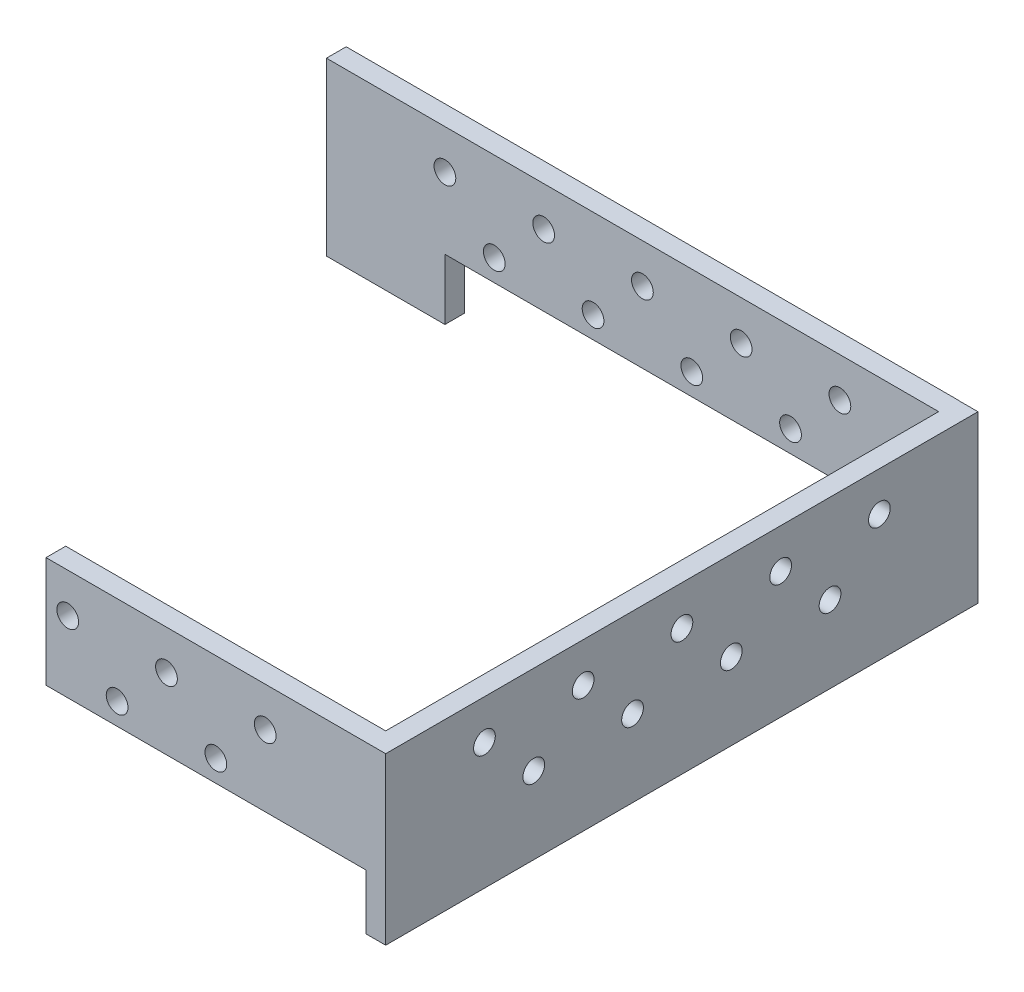
SolidWorks part; units mm, degrees
ref_plane "Front Plane" through (0, 0, 0) normal (0, 0, 1) x (1, 0, 0)
ref_plane "Top Plane" through (0, 0, 0) normal (0, 1, 0) x (1, 0, 0)
ref_plane "Right Plane" through (0, 0, 0) normal (1, 0, 0) x (0, 0, -1)
ref_plane "Plane1" through (-5, 0, 0) normal (-1, 0, 0) x (0, -1, 0)
sketch "Sketch1" plane through (-5, 0, 0) normal (-1, 0, 0) x (0, -1, 0)
  line L0 (42, 0) -> (0, 0)
  line L1 (0, 0) -> (0, -145.1613)
  line L2 (0, -145.1613) -> (42, -145.1613)
  line L3 (42, -145.1613) -> (42, 0)
  dimension "D1" = 42
extrude "Boss-Extrude1" add sketch "Sketch1" against normal blind 5
ref_plane "Plane2" through (0, 0, -150) normal (0, 0, -1) x (-1, 0, 0)
sketch "Sketch2" plane through (0, 0, -150) normal (0, 0, -1) x (-1, 0, 0)
  line L0 (130, -43.4) -> (160, -43.4)
  line L1 (160, -43.4) -> (160, 0)
  line L2 (160, 0) -> (5, 0)
  line L3 (5, 0) -> (5, -28)
  line L4 (5, -28) -> (130, -28)
  line L5 (130, -28) -> (130, -43.4)
extrude "Boss-Extrude2" add sketch "Sketch2" against normal blind 5
sketch "Sketch3" plane through (-5, 0, 0) normal (-1, 0, 0) x (0, 0, 1)
  line L0 (0, -28) -> (-5, -28)
  line L1 (-5, -28) -> (-5, 0)
  line L2 (-5, 0) -> (0, 0)
  line L3 (0, 0) -> (0, -28)
extrude "Boss-Extrude3" add sketch "Sketch3" along normal blind 81
hole_wizard "Ø5.5 (5.5) Diameter Hole1" positions "Sketch5" profile "Sketch4" hole size "Ø5.5" standard "ANSI Metric" end condition through all
sketch "Sketch5" plane through (-5, 0, 0) normal (-1, 0, 0) x (0, 0, 1)
  point P0 (-37.5, -22.5)
  point P1 (-25, -10)
  point P2 (-50, -10)
  point P3 (-62.5, -22.5)
  point P4 (-75, -10)
  point P5 (-87.5, -22.5)
  point P6 (-112.5, -22.5)
  point P7 (-100, -10)
  point P8 (-125, -10)
sketch "Sketch4" plane through (-5, -22.5, -37.5) normal (0, 1, 0) x (0, 0, 1)
  line L0 (0, 0) -> (0, 5)
  line L1 (0, 5) -> (2.75, 5)
  line L2 (2.75, 5) -> (2.75, 0)
  line L5 (2.75, 0) -> (0, 0)
  line L11 (0, -6.35) -> (0, 107.95) construction
  dimension "Thru Hole Dia." = 5.5
  dimension "Thru Hole Depth" = 5
hole_wizard "Ø5.5 (5.5) Diameter Hole2" positions "Sketch7" profile "Sketch6" hole size "Ø5.5" standard "ANSI Metric"
sketch "Sketch7" plane through (0, 0, -145) normal (0, 0, 1) x (1, 0, 0)
  point P0 (-30, -10)
  point P1 (-42.5, -22.5)
  point P2 (-67.5, -22.5)
  point P3 (-55, -10)
  point P4 (-80, -10)
  point P5 (-92.5, -22.5)
  point P6 (-117.5, -22.5)
  point P7 (-105, -10)
  point P8 (-130, -10)
sketch "Sketch6" plane through (-30, -10, -145) normal (1, 0, 0) x (0, -1, 0)
  line L0 (0, 0) -> (0, 5)
  line L1 (0, 5) -> (2.75, 5)
  line L2 (2.75, 5) -> (2.75, 0)
  line L5 (2.75, 0) -> (0, 0)
  line L11 (0, -6.35) -> (0, 107.95) construction
  dimension "Thru Hole Dia." = 5.5
  dimension "Thru Hole Depth" = 5
hole_wizard "Ø5.5 (5.5) Diameter Hole3" positions "Sketch9" profile "Sketch8" hole size "Ø5.5" standard "ANSI Metric"
sketch "Sketch9" plane through (0, 0, -5) normal (0, 0, -1) x (-1, 0, 0)
  point P0 (80.5, -10)
  point P1 (68, -22.5)
  point P2 (43, -22.5)
  point P3 (55.5, -10)
  point P4 (30.5, -10)
sketch "Sketch8" plane through (-80.5, -10, -5) normal (1, 0, 0) x (0, 1, 0)
  line L0 (0, 0) -> (0, 5)
  line L1 (0, 5) -> (2.75, 5)
  line L2 (2.75, 5) -> (2.75, 0)
  line L5 (2.75, 0) -> (0, 0)
  line L11 (0, -6.35) -> (0, 107.95) construction
  dimension "Thru Hole Dia." = 5.5
  dimension "Thru Hole Depth" = 5
sketch "Sketch10" plane through (0, 0, -145.1613) normal (0, 0, -1) x (-1, 0, 0)
  line L0 (0, 0) -> (5, 0)
  line L1 (5, 0) -> (5, -42)
  line L2 (5, -42) -> (0, -42)
  line L3 (0, -42) -> (0, 0)
extrude "Boss-Extrude4" add sketch "Sketch10" along normal blind 4.8
